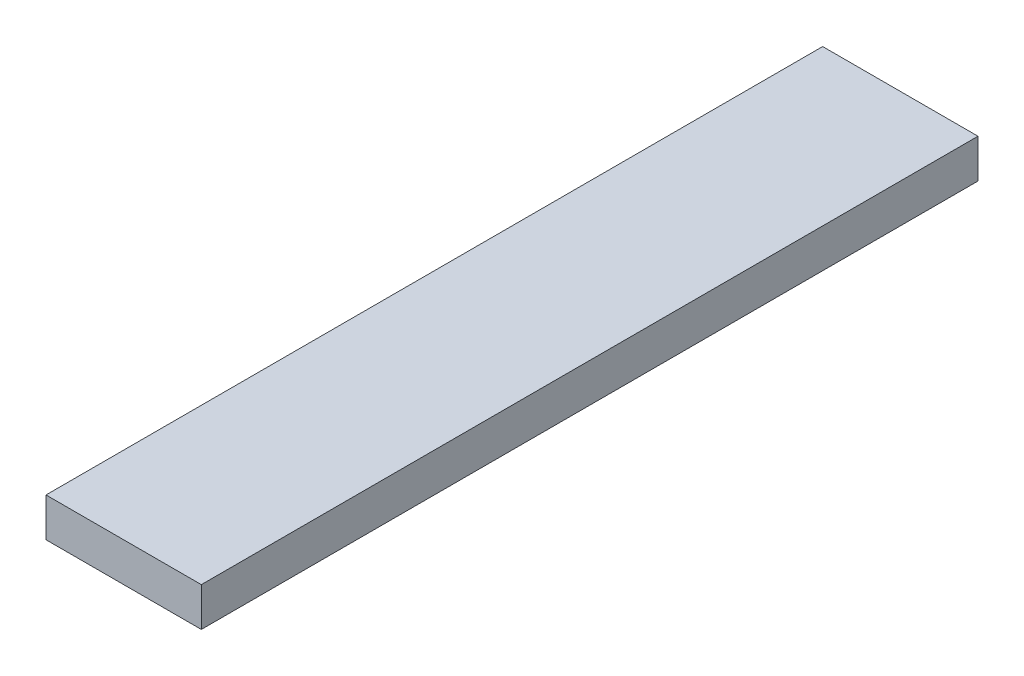
SolidWorks part; units mm, degrees
material "Beech"
ref_plane "Front Plane" through (0, 0, 0) normal (0, 0, 1) x (1, 0, 0)
ref_plane "Top Plane" through (0, 0, 0) normal (0, 1, 0) x (1, 0, 0)
ref_plane "Right Plane" through (0, 0, 0) normal (1, 0, 0) x (0, 0, -1)
sketch "Sketch1" plane through (0, 0, 0) normal (0, 1, 0) x (1, 0, 0)
  line L1 (0, 0) -> (304.8, 0)
  line L2 (0, 0) -> (0, 304.8)
  line L3 (0, 304.8) -> (304.8, 304.8)
  line L4 (304.8, 0) -> (304.8, 304.8)
  dimension "D1" = 304.8
  dimension "D2" = 304.8
extrude "Boss-Extrude1" add sketch "Sketch1" along normal blind 6.35
sketch "Sketch2" plane through (0, 6.35, 0) normal (0, 1, 0) x (1, 0, 0)
  line L1 (304.8, 304.8) -> (0, 304.8) construction
  line L2 (25.4, 304.8) -> (25.4, 177.8)
  line L3 (25.4, 177.8) -> (0, 177.8)
  line L4 (0, 304.8) -> (0, 0) construction
  line L6 (0, 177.8) -> (0, 0)
  line L7 (0, 0) -> (304.8, 0)
  line L8 (304.8, 0) -> (304.8, 304.8)
  line L9 (304.8, 304.8) -> (25.4, 304.8)
  dimension "D1" = 25.4
  dimension "D2" = 127
extrude "Cut-Extrude2" cut sketch "Sketch2" against normal blind 6.35 contours L3 L6 L7 L8 L9 L2
